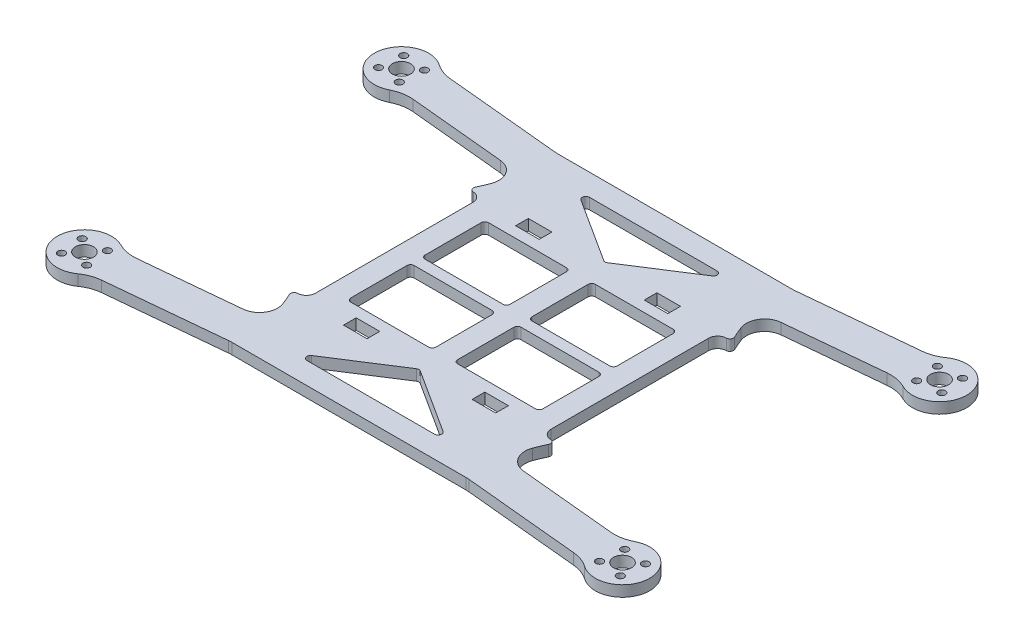
SolidWorks part; units mm, degrees
ref_plane "Front Plane" through (0, 0, 0) normal (0, 0, 1) x (1, 0, 0)
ref_plane "Top Plane" through (0, 0, 0) normal (0, 1, 0) x (1, 0, 0)
ref_plane "Right Plane" through (0, 0, 0) normal (1, 0, 0) x (0, 0, -1)
sketch "Sketch1" plane through (0, 0, 0) normal (0, 1, 0) x (1, 0, 0)
  line L0 (-492.3952, 0) -> (24127.3654, 0) construction
  line L1 (0, -492.3952) -> (0, 24127.3654) construction
  line L2 (-32.25, 45) -> (32.25, 45)
  line L3 (33.2085, 45.046) -> (65.1584, 48.1225)
  line L4 (32.5, -21.7401) -> (32.5, 21.7401)
  line L5 (65.3748, 38.0971) -> (38.6712, 35.5258)
  line L6 (70.7777, 46.6124) -> (74.25, 43.75) construction
  line L7 (-17.6, 39) -> (17.6, 39)
  line L8 (4, 1.5) -> (25.5, 1.5)
  line L9 (3, 2.5) -> (3, 18)
  line L10 (4, 19) -> (25.5, 19)
  line L11 (26.5, 2.5) -> (26.5, 18)
  line L12 (14.5, 22) -> (21, 22)
  line L13 (14.5, 22) -> (14.5, 25.5)
  line L14 (14.5, 25.5) -> (21, 25.5)
  line L15 (21, 22) -> (21, 25.5)
  line L16 (18.1402, 37.1585) -> (0.5402, 25.8595)
  line L17 (-70.7777, 46.6124) -> (-74.25, 43.75) construction
  line L18 (-18.1402, 37.1585) -> (-0.5402, 25.8595)
  line L19 (-21, 22) -> (-21, 25.5)
  line L20 (-14.5, 25.5) -> (-21, 25.5)
  line L21 (-14.5, 22) -> (-14.5, 25.5)
  line L22 (-14.5, 22) -> (-21, 22)
  line L23 (-26.5, 2.5) -> (-26.5, 18)
  line L24 (-4, 19) -> (-25.5, 19)
  line L25 (-3, 2.5) -> (-3, 18)
  line L26 (-4, 1.5) -> (-25.5, 1.5)
  line L27 (-65.3748, 38.0971) -> (-38.6712, 35.5258)
  line L28 (-32.5, -21.7401) -> (-32.5, 21.7401)
  line L29 (-33.2085, 45.046) -> (-65.1584, 48.1225)
  line L30 (-70.7777, -46.6124) -> (-74.25, -43.75) construction
  line L31 (70.7777, -46.6124) -> (74.25, -43.75) construction
  line L32 (-33.2085, -45.046) -> (-65.1584, -48.1225)
  line L33 (-65.3748, -38.0971) -> (-38.6712, -35.5258)
  line L34 (-4, -1.5) -> (-25.5, -1.5)
  line L35 (-3, -2.5) -> (-3, -18)
  line L36 (-4, -19) -> (-25.5, -19)
  line L37 (-26.5, -2.5) -> (-26.5, -18)
  line L38 (-14.5, -22) -> (-21, -22)
  line L39 (-14.5, -22) -> (-14.5, -25.5)
  line L40 (-14.5, -25.5) -> (-21, -25.5)
  line L41 (-21, -22) -> (-21, -25.5)
  line L42 (-18.1402, -37.1585) -> (-0.5402, -25.8595)
  line L43 (18.1402, -37.1585) -> (0.5402, -25.8595)
  line L44 (21, -22) -> (21, -25.5)
  line L45 (14.5, -25.5) -> (21, -25.5)
  line L46 (14.5, -22) -> (14.5, -25.5)
  line L47 (14.5, -22) -> (21, -22)
  line L48 (26.5, -2.5) -> (26.5, -18)
  line L49 (4, -19) -> (25.5, -19)
  line L50 (3, -2.5) -> (3, -18)
  line L51 (4, -1.5) -> (25.5, -1.5)
  line L52 (-17.6, -39) -> (17.6, -39)
  line L53 (65.3748, -38.0971) -> (38.6712, -35.5258)
  line L54 (33.2085, -45.046) -> (65.1584, -48.1225)
  line L55 (-32.25, -45) -> (32.25, -45)
  circle A0 centre (74.25, 43.75) radius 2.5
  arc A1 (70.8571, 37.0613) -> (69.9428, 49.8899) centre (74.25, 43.75) ccw
  arc A2 (32.25, 45) -> (33.2085, 45.046) centre (32.25, 55) ccw
  arc A3 (32.5, 21.7401) -> (34.9182, 24.2387) centre (35, 21.7401) cw
  arc A4 (35.7904, 25.6637) -> (34.9182, 24.2387) centre (34.8855, 25.2382) cw
  arc A5 (34.4705, 28.7887) -> (35.7904, 25.6637) centre (74.25, 43.75) ccw
  arc A6 (38.6712, 35.5258) -> (34.4705, 28.7887) centre (39.1504, 30.5488) ccw
  circle A7 centre (70.7777, 46.6124) radius 1
  arc A8 (25.5, 1.5) -> (26.5, 2.5) centre (25.5, 2.5) ccw
  arc A9 (25.5, 19) -> (26.5, 18) centre (25.5, 18) cw
  arc A10 (3, 18) -> (4, 19) centre (4, 18) cw
  arc A11 (4, 1.5) -> (3, 2.5) centre (4, 2.5) cw
  circle A12 centre (77.1124, 47.2223) radius 1
  circle A13 centre (77.7223, 40.8876) radius 1
  circle A14 centre (71.3876, 40.2777) radius 1
  circle A15 centre (-71.3876, 40.2777) radius 1
  circle A16 centre (-77.7223, 40.8876) radius 1
  circle A17 centre (-77.1124, 47.2223) radius 1
  arc A18 (-4, 1.5) -> (-3, 2.5) centre (-4, 2.5) ccw
  arc A19 (-3, 18) -> (-4, 19) centre (-4, 18) ccw
  arc A20 (-25.5, 19) -> (-26.5, 18) centre (-25.5, 18) ccw
  arc A21 (-25.5, 1.5) -> (-26.5, 2.5) centre (-25.5, 2.5) cw
  circle A22 centre (-70.7777, 46.6124) radius 1
  arc A23 (-38.6712, 35.5258) -> (-34.4705, 28.7887) centre (-39.1504, 30.5488) cw
  arc A24 (-34.4705, 28.7887) -> (-35.7904, 25.6637) centre (-74.25, 43.75) cw
  arc A25 (-35.7904, 25.6637) -> (-34.9182, 24.2387) centre (-34.8855, 25.2382) ccw
  arc A26 (-32.5, 21.7401) -> (-34.9182, 24.2387) centre (-35, 21.7401) ccw
  arc A27 (-32.25, 45) -> (-33.2085, 45.046) centre (-32.25, 55) cw
  arc A28 (-70.8571, 37.0613) -> (-69.9428, 49.8899) centre (-74.25, 43.75) cw
  circle A29 centre (-74.25, 43.75) radius 2.5
  arc A30 (17.6, 39) -> (18.1402, 37.1585) centre (17.6, 38) cw
  arc A31 (-18.1402, 37.1585) -> (-17.6, 39) centre (-17.6, 38) cw
  arc A32 (0.5402, 25.8595) -> (-0.5402, 25.8595) centre (0, 26.701) cw
  arc A33 (0.5402, -25.8595) -> (-0.5402, -25.8595) centre (0, -26.701) ccw
  arc A34 (-18.1402, -37.1585) -> (-17.6, -39) centre (-17.6, -38) ccw
  arc A35 (17.6, -39) -> (18.1402, -37.1585) centre (17.6, -38) ccw
  circle A36 centre (-74.25, -43.75) radius 2.5
  arc A37 (-70.8571, -37.0613) -> (-69.9428, -49.8899) centre (-74.25, -43.75) ccw
  arc A38 (-32.25, -45) -> (-33.2085, -45.046) centre (-32.25, -55) ccw
  arc A39 (-32.5, -21.7401) -> (-34.9182, -24.2387) centre (-35, -21.7401) cw
  arc A40 (-35.7904, -25.6637) -> (-34.9182, -24.2387) centre (-34.8855, -25.2382) cw
  arc A41 (-34.4705, -28.7887) -> (-35.7904, -25.6637) centre (-74.25, -43.75) ccw
  arc A42 (-38.6712, -35.5258) -> (-34.4705, -28.7887) centre (-39.1504, -30.5488) ccw
  circle A43 centre (-70.7777, -46.6124) radius 1
  arc A44 (-25.5, -1.5) -> (-26.5, -2.5) centre (-25.5, -2.5) ccw
  arc A45 (-25.5, -19) -> (-26.5, -18) centre (-25.5, -18) cw
  arc A46 (-3, -18) -> (-4, -19) centre (-4, -18) cw
  arc A47 (-4, -1.5) -> (-3, -2.5) centre (-4, -2.5) cw
  circle A48 centre (-77.1124, -47.2223) radius 1
  circle A49 centre (-77.7223, -40.8876) radius 1
  circle A50 centre (-71.3876, -40.2777) radius 1
  circle A51 centre (71.3876, -40.2777) radius 1
  circle A52 centre (77.7223, -40.8876) radius 1
  circle A53 centre (77.1124, -47.2223) radius 1
  arc A54 (4, -1.5) -> (3, -2.5) centre (4, -2.5) ccw
  arc A55 (3, -18) -> (4, -19) centre (4, -18) ccw
  arc A56 (25.5, -19) -> (26.5, -18) centre (25.5, -18) ccw
  arc A57 (25.5, -1.5) -> (26.5, -2.5) centre (25.5, -2.5) cw
  circle A58 centre (70.7777, -46.6124) radius 1
  arc A59 (38.6712, -35.5258) -> (34.4705, -28.7887) centre (39.1504, -30.5488) cw
  arc A60 (34.4705, -28.7887) -> (35.7904, -25.6637) centre (74.25, -43.75) cw
  arc A61 (35.7904, -25.6637) -> (34.9182, -24.2387) centre (34.8855, -25.2382) ccw
  arc A62 (32.5, -21.7401) -> (34.9182, -24.2387) centre (35, -21.7401) ccw
  arc A63 (32.25, -45) -> (33.2085, -45.046) centre (32.25, -55) cw
  arc A64 (70.8571, -37.0613) -> (69.9428, -49.8899) centre (74.25, -43.75) cw
  circle A65 centre (74.25, -43.75) radius 2.5
  arc A66 (70.8571, -37.0613) -> (65.3748, -38.0971) centre (66.3333, -28.1431) cw
  arc A67 (69.9428, -49.8899) -> (65.1584, -48.1225) centre (64.2, -58.0764) ccw
  arc A68 (-70.8571, -37.0613) -> (-65.3748, -38.0971) centre (-66.3333, -28.1431) ccw
  arc A69 (-69.9428, -49.8899) -> (-65.1584, -48.1225) centre (-64.2, -58.0764) cw
  arc A70 (-69.9428, 49.8899) -> (-65.1584, 48.1225) centre (-64.2, 58.0764) ccw
  arc A71 (-70.8571, 37.0613) -> (-65.3748, 38.0971) centre (-66.3333, 28.1431) cw
  arc A72 (65.3748, 38.0971) -> (70.8571, 37.0613) centre (66.3333, 28.1431) cw
  arc A73 (65.1584, 48.1225) -> (69.9428, 49.8899) centre (64.2, 58.0764) ccw
  point P8 (-74.25, 43.75)
  point P10 (0, -25.5127)
  point P37 (26.5, 1.5)
  point P40 (26.5, 19)
  point P45 (3, 1.5)
  point P46 (66.7714, 35.5258)
  point P47 (0, 0)
  point P55 (74.25, 43.75)
  point P95 (0, 39)
  point P96 (0, 45)
  point P97 (-3, 1.5)
  point P98 (-26.5, 19)
  point P99 (-26.5, 1.5)
  point P102 (21.0087, 39)
  point P105 (-21.0087, 39)
  point P108 (0, 25.5127)
  point P188 (-32.5, 0)
  point P196 (32.5, 0)
  point P197 (-21.0087, -39)
  point P198 (21.0087, -39)
  point P199 (-26.5, -1.5)
  point P200 (-26.5, -19)
  point P201 (-3, -1.5)
  point P202 (0, -45)
  point P203 (0, -39)
  point P204 (74.25, -43.75)
  point P205 (3, -1.5)
  point P206 (26.5, -19)
  point P207 (26.5, -1.5)
  point P208 (-74.25, -43.75)
  point P211 (68.9519, -38.4415)
  point P214 (68.3924, -48.4339)
  point P217 (-68.9519, -38.4415)
  point P220 (-68.3924, -48.4339)
  point P223 (-68.3924, 48.4339)
  point P226 (-68.9519, 38.4415)
  point P229 (68.9519, 38.4415)
  point P232 (68.3924, 48.4339)
  dimension "D1" = 5
  dimension "D2" = 15
  dimension "D3" = 163.5
  dimension "D4" = 102.5
  dimension "D7" = 10
  dimension "D10" = 2.5
  dimension "D11" = 1
  dimension "D12" = 42.5
  dimension "D13" = 5
  dimension "D15" = 2
  dimension "D16" = 45
  dimension "D28" = 1
  dimension "D30" = 1
  dimension "D32" = 10
  dimension "D5" = 10
  dimension "D6" = 174.5
  dimension "D8" = 64.5
  dimension "D9" = 32.5
  dimension "D14" = 45
  dimension "D17" = 4.5
  dimension "D18" = 6
  dimension "D19" = 32.7
  dimension "D20" = 3.5
  dimension "D21" = 6.5
  dimension "D22" = 14.5
  dimension "D23" = 22
  dimension "D24" = 1.5
  dimension "D25" = 23.5
  dimension "D26" = 17.5
  dimension "D27" = 6
  dimension "D31" = 17.6
  dimension "D29" = 4
extrude "Boss-Extrude1" add sketch "Sketch1" along normal blind 3
